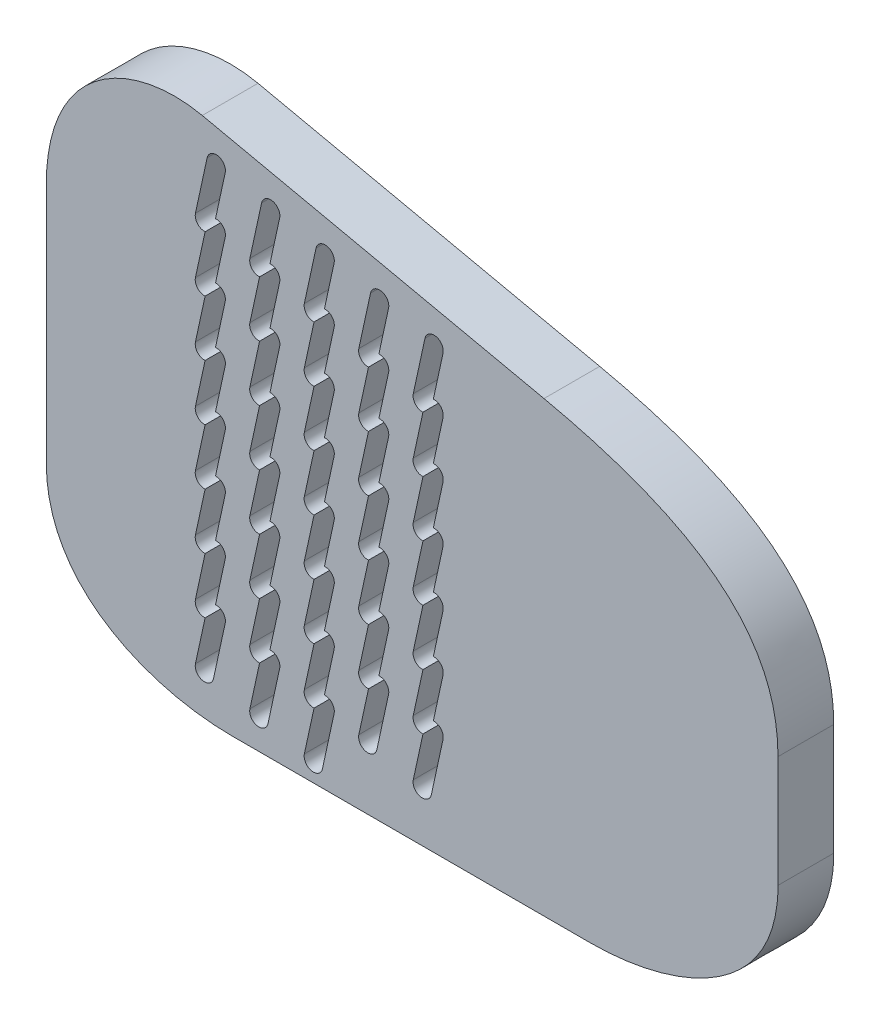
SolidWorks part; units mm, degrees
ref_plane "Спереди" through (0, 0, 0) normal (0, 0, 1) x (1, 0, 0)
ref_plane "Сверху" through (0, 0, 0) normal (0, 1, 0) x (1, 0, 0)
ref_plane "Справа" through (0, 0, 0) normal (1, 0, 0) x (0, 0, -1)
sketch "Эскиз1_fr" plane through (0, 0, 0) normal (0, 0, 1) x (1, 0, 0)
  line L0 (0, 0) -> (0, 20)
  line L1 (-41.9869, 54.6497) -> (-103.3012, 67.9789)
  line L2 (-131.2925, 43.0977) -> (-131.2925, 0)
  line L3 (-33.5451, -25.7698) -> (-97.9695, -25.7698)
  spline S0 degree 3 poles (0, 20) (0, 38.146) (-14.2095, 48.6111) (-41.9869, 54.6497) knots 0 0 0 0 1 1 1 1
  spline S1 degree 3 poles (-103.3012, 67.9789) (-115.5, 70.6308) (-131.2925, 63.3933) (-131.2925, 43.0977) knots 0 0 0 0 1 1 1 1
  spline S2 degree 3 poles (-33.5451, -25.7698) (-19.4449, -25.7698) (0, -19.0638) (0, 0) knots 0 0 0 0 1 1 1 1
  spline S3 degree 3 poles (-97.9695, -25.7698) (-112.0112, -25.7698) (-131.2925, -19.0252) (-131.2925, 0) knots 0 0 0 0 1 1 1 1
  dimension "D1" = 20
extrude "Бобышка-Вытянуть1" add sketch "Эскиз1_fr" along normal blind 10
sketch "Эскиз2_fr" plane through (0, 0, 0) normal (0, 0, -1) x (-1, 0, 0)
  line L2 (100.8084, 61.4805) -> (102.9069, 51.8273) construction
  line L3 (102.4293, 61.8329) -> (104.5278, 52.1796)
  line L4 (99.1876, 61.1282) -> (101.2861, 51.4749)
  arc A0 (102.4293, 61.8329) -> (99.1876, 61.1282) centre (100.8084, 61.4805) ccw
  arc A1 (101.2861, 51.4749) -> (104.5278, 52.1796) centre (102.9069, 51.8273) ccw
  point P4 (101.8577, 56.6539)
extrude "Вырез-Вытянуть1" cut sketch "Эскиз2_fr" against normal through all contours L3 A1 L4 A0
pattern_linear "Линейный массив1" count 5 spacing 10 along (0.9772, -0.2124, 0) count 9 spacing 10 along (0, -1, 0) skipping (0, 8), (1, 8), (2, 8), (3, 7), (3, 8), (4, 7), (4, 8) of "Вырез-Вытянуть1"
